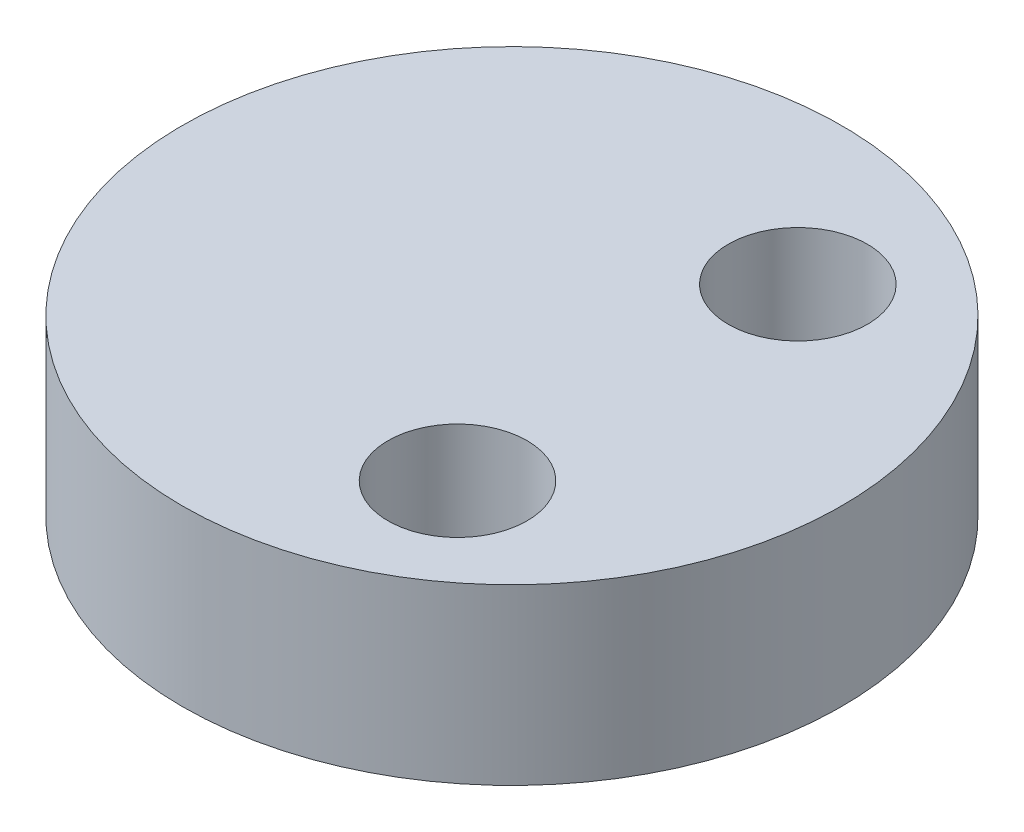
SolidWorks part; units mm, degrees
ref_plane "Front Plane" through (0, 0, 0) normal (0, 0, 1) x (1, 0, 0)
ref_plane "Top Plane" through (0, 0, 0) normal (0, 1, 0) x (1, 0, 0)
ref_plane "Right Plane" through (0, 0, 0) normal (1, 0, 0) x (0, 0, -1)
sketch "Sketch1" plane through (0, 0, 0) normal (0, 1, 0) x (1, 0, 0)
  circle A0 centre (0, 0) radius 9.48
  dimension "D1" = 18.96
extrude "Boss-Extrude1" add sketch "Sketch1" against normal blind 5
sketch "Sketch2" plane through (0, 0, 0) normal (0, 1, 0) x (1, 0, 0)
  line L0 (-11.6497, 0) -> (12.3217, 0) construction
  circle A1 centre (3.3293, 4.8945) radius 2
  circle A2 centre (3.3293, -4.8945) radius 2
extrude "Cut-Extrude1" cut sketch "Sketch2" against normal blind 3
sketch "Sketch3" plane through (0, 0, 0) normal (0, 0, 1) x (1, 0, 0)
  line L0 (9.48, 0) -> (-9.48, 0) construction
  circle A0 centre (0, -2.5) radius 2.0554
  dimension "D1" = 2.5
